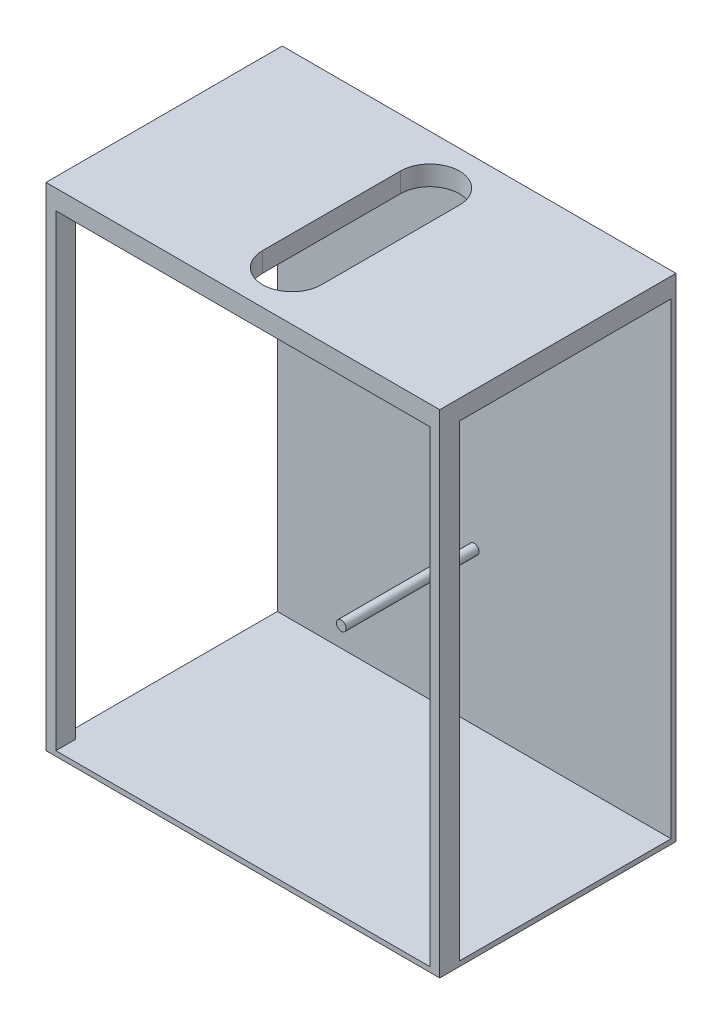
SolidWorks part; units mm, degrees
ref_plane "Front Plane" through (0, 0, 0) normal (0, 0, 1) x (1, 0, 0)
ref_plane "Top Plane" through (0, 0, 0) normal (0, 1, 0) x (1, 0, 0)
ref_plane "Right Plane" through (0, 0, 0) normal (1, 0, 0) x (0, 0, -1)
sketch "Sketch1" plane through (0, 0, 0) normal (0, 0, 1) x (1, 0, 0)
  line L1 (0, 0) -> (508, 0)
  line L2 (0, 0) -> (0, 635)
  line L3 (0, 635) -> (508, 635)
  line L4 (508, 0) -> (508, 635)
  dimension "D1" = 635
  dimension "D2" = 508
extrude "Boss-Extrude1" add sketch "Sketch1" along normal blind 6.35
sketch "Sketch2" plane through (0, 0, 0) normal (0, 0, 1) x (1, 0, 0)
  line L0 (0, 0) -> (508, 0) construction
  line L1 (508, 635) -> (0, 635) construction
  circle A0 centre (254, 203.2) radius 6.35
  point P4 (254, 0)
  dimension "D2" = 12.7
  dimension "D1" = 431.8
extrude "Boss-Extrude2" add sketch "Sketch2" along normal blind 177.8
sketch "Sketch3" plane through (0, 0, 0) normal (0, 1, 0) x (1, 0, 0)
  line L1 (0, -6.35) -> (508, -6.35)
  line L2 (0, -6.35) -> (0, -304.8)
  line L3 (0, -304.8) -> (508, -304.8)
  line L4 (508, -6.35) -> (508, -304.8)
  line L5 (247.65, -177.8) -> (260.35, -177.8) construction
  dimension "D1" = 127
extrude "Boss-Extrude3" add sketch "Sketch3" along normal blind 6.35
sketch "Sketch4" plane through (0, 0, 0) normal (1, 0, 0) x (0, 0, -1)
  line L0 (-304.8, 6.35) -> (-304.8, 635)
  line L1 (-304.8, 635) -> (-6.35, 635)
  line L2 (-6.35, 635) -> (-6.35, 609.6)
  line L4 (-304.8, 6.35) -> (-6.35, 6.35) construction
  line L6 (-6.35, 609.6) -> (-279.4, 609.6)
  line L7 (-6.35, 635) -> (-6.35, 6.35) construction
  line L8 (-279.4, 609.6) -> (-279.4, 6.35)
  line L9 (-279.4, 6.35) -> (-304.8, 6.35)
  dimension "D1" = 25.4
  dimension "D2" = 25.4
extrude "Boss-Extrude4" add sketch "Sketch4" along normal blind 12.7
sketch "Sketch5" plane through (0, 0, 0) normal (0, 0, 1) x (1, 0, 0)
  line L0 (254, 635) -> (254, 0) construction
  line L6 (0, 0) -> (508, 0) construction
  line L7 (508, 635) -> (0, 635) construction
  point P2 (191.4597, 631.9795)
  point P4 (260.35, 635)
  point P6 (254, 635)
  point P9 (254, 0)
ref_plane "Plane1" through (254, 0, 0) normal (1, 0, 0) x (0, 0, -1)
mirror "Mirror1" about plane through (254, 0, 0) normal (1, 0, 0) of "Boss-Extrude4"
ref_plane "Plane2" through (12.7, 0, 0) normal (1, 0, 0) x (0, 0, -1)
sketch "Sketch6" plane through (12.7, 0, 0) normal (1, 0, 0) x (0, 0, -1)
  line L1 (-304.8, 635) -> (-6.35, 635)
  line L2 (-304.8, 635) -> (-304.8, 609.6)
  line L3 (-304.8, 609.6) -> (-6.35, 609.6)
  line L4 (-6.35, 635) -> (-6.35, 609.6)
  point P5 (-233.5685, 563.7685)
  point P6 (-6.35, 609.6)
extrude "Boss-Extrude6" add sketch "Sketch6" along normal up to surface (482.6 mm away) up to face at (495.3, 416.9833, 196.85)
ref_plane "Plane3" through (0, 635, 0) normal (0, 1, 0) x (1, 0, 0)
sketch "Sketch7" plane through (0, 635, 0) normal (0, 1, 0) x (1, 0, 0)
  line L0 (508, 0) -> (0, 0) construction
  line L1 (254, 0) -> (254, -304.8) construction
  line L2 (508, -304.8) -> (0, -304.8) construction
  line L3 (0, -152.4) -> (508, -152.4) construction
  line L4 (0, -304.8) -> (0, 0) construction
  line L5 (508, -304.8) -> (508, 0) construction
  line L6 (254, -63.5) -> (254, -241.3) construction
  line L7 (292.1, -63.5) -> (292.1, -241.3)
  line L8 (215.9, -63.5) -> (215.9, -241.3)
  arc A1 (292.1, -63.5) -> (215.9, -63.5) centre (254, -63.5) ccw
  arc A2 (215.9, -241.3) -> (292.1, -241.3) centre (254, -241.3) ccw
  point P15 (254, -152.4)
  point P20 (215.9, -243.7084)
  dimension "D1" = 76.2
  dimension "D2" = 177.8
extrude "Cut-Extrude1" cut sketch "Sketch7" against normal up to surface (25.4 mm away) up to face at (254, 609.6, 217.4875)
